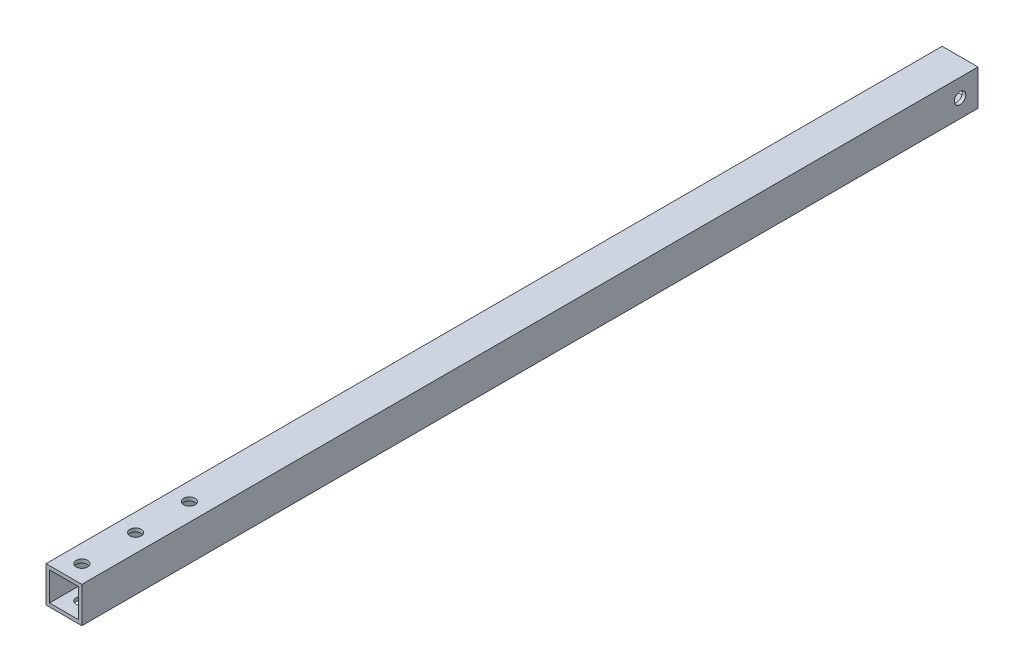
SolidWorks part; units mm, degrees
ref_plane "Front Plane" through (0, 0, 0) normal (0, 0, 1) x (1, 0, 0)
ref_plane "Top Plane" through (0, 0, 0) normal (0, 1, 0) x (1, 0, 0)
ref_plane "Right Plane" through (0, 0, 0) normal (1, 0, 0) x (0, 0, -1)
sketch "ｽｹｯﾁ1" plane through (0, 0, 0) normal (0, 0, 1) x (1, 0, 0)
  line L1 (5, -5) -> (-5, -5)
  line L2 (5, -5) -> (5, 5)
  line L3 (5, 5) -> (-5, 5)
  line L4 (-5, -5) -> (-5, 5)
  line L5 (5, -5) -> (-5, 5) construction
  line L6 (5, 5) -> (-5, -5) construction
  line L7 (4, -4) -> (-4, -4)
  line L8 (4, -4) -> (4, 4)
  line L9 (4, 4) -> (-4, 4)
  line L10 (-4, -4) -> (-4, 4)
  line L11 (4, -4) -> (-4, 4) construction
  line L12 (4, 4) -> (-4, -4) construction
  point P0 (0, 0)
  point P6 (0, 0)
  dimension "D1" = 10
  dimension "D2" = 10
  dimension "D3" = 1
extrude "ﾎﾞｽ - 押し出し1" add sketch "ｽｹｯﾁ1" along normal blind 250
sketch "ｽｹｯﾁ2" plane through (0, 5, 0) normal (0, 1, 0) x (1, 0, 0)
  line L1 (5, -250) -> (5, 0) construction
  line L2 (5, -250) -> (-5, -250) construction
  circle A0 centre (0, -215) radius 1.6
  circle A1 centre (0, -245) radius 1.6
  circle A2 centre (0, -230) radius 1.6
  dimension "D1" = 3.2
  dimension "D2" = 3.2
  dimension "D3" = 3.2
  dimension "D4" = 5
  dimension "D5" = 15
  dimension "D6" = 15
  dimension "D7" = 5
  dimension "D8" = 5
  dimension "D9" = 5
extrude "ｶｯﾄ - 押し出し1" cut sketch "ｽｹｯﾁ2" against normal through all
sketch "ｽｹｯﾁ3" plane through (5, 0, 0) normal (1, 0, 0) x (0, 0, -1)
  line L0 (-250, 5) -> (0, 5) construction
  line L2 (0, -5) -> (0, 5) construction
  circle A0 centre (-5, 0) radius 1.6
  dimension "D1" = 3.2
  dimension "D3" = 5
  dimension "D2" = 5
extrude "ｶｯﾄ - 押し出し2" cut sketch "ｽｹｯﾁ3" against normal blind 60
